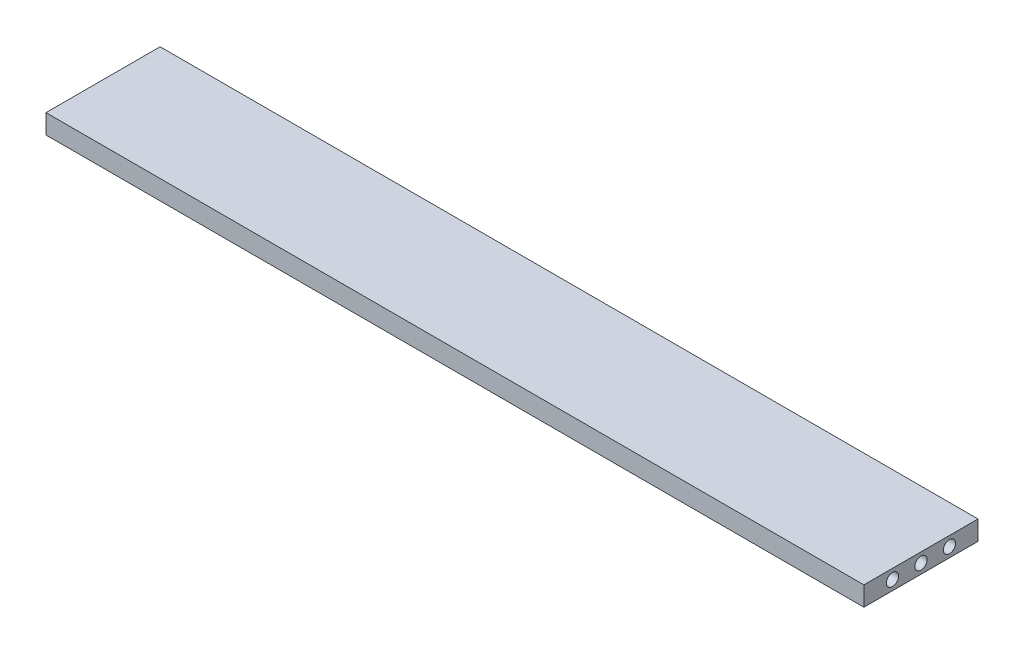
SolidWorks part; units mm, degrees
ref_plane "Plano frontal" through (0, 0, 0) normal (0, 0, 1) x (1, 0, 0)
ref_plane "Plano superior" through (0, 0, 0) normal (0, 1, 0) x (1, 0, 0)
ref_plane "Plano direito" through (0, 0, 0) normal (1, 0, 0) x (0, 0, -1)
sketch "Esboço1" plane through (0, 0, 0) normal (0, 1, 0) x (1, 0, 0)
  line L0 (200.715, 28) -> (-200.715, -28) construction
  line L1 (-200.715, 28) -> (200.715, 28)
  line L2 (-200.715, 28) -> (-200.715, -28)
  line L3 (-200.715, -28) -> (200.715, -28)
  line L4 (200.715, 28) -> (200.715, -28)
  line L5 (-200.715, -28) -> (-200.707, -28.2845) construction
  dimension "D1" = 401.43
  dimension "D2" = 56
extrude "Ressalto-extrusão1" add sketch "Esboço1" along normal blind 9.525
sketch "Esboço2" plane through (-200.715, 0, 0) normal (-1, 0, 0) x (0, 0, 1)
  line L0 (-14, 4.76) -> (14, 4.76) construction
  circle A0 centre (14, 4.76) radius 3
  circle A1 centre (0, 4.76) radius 3
  circle A2 centre (-14, 4.76) radius 3
  dimension "D1" = 6
  dimension "D2" = 6
  dimension "D3" = 6
  dimension "D4" = 4.76
  dimension "D5" = 14
  dimension "D6" = 14
extrude "Furos Izq" cut sketch "Esboço2" against normal blind 30
sketch "Esboço3" plane through (200.715, 0, 0) normal (1, 0, 0) x (0, 0, -1)
  line L0 (-14, 4.765) -> (14, 4.765) construction
  circle A0 centre (14, 4.765) radius 3
  circle A1 centre (0, 4.765) radius 3
  circle A2 centre (-14, 4.765) radius 3
  dimension "D1" = 6
  dimension "D2" = 6
  dimension "D3" = 6
  dimension "D4" = 14
  dimension "D5" = 14
  dimension "D6" = 4.76
extrude "Furos Der" cut sketch "Esboço3" against normal blind 30
